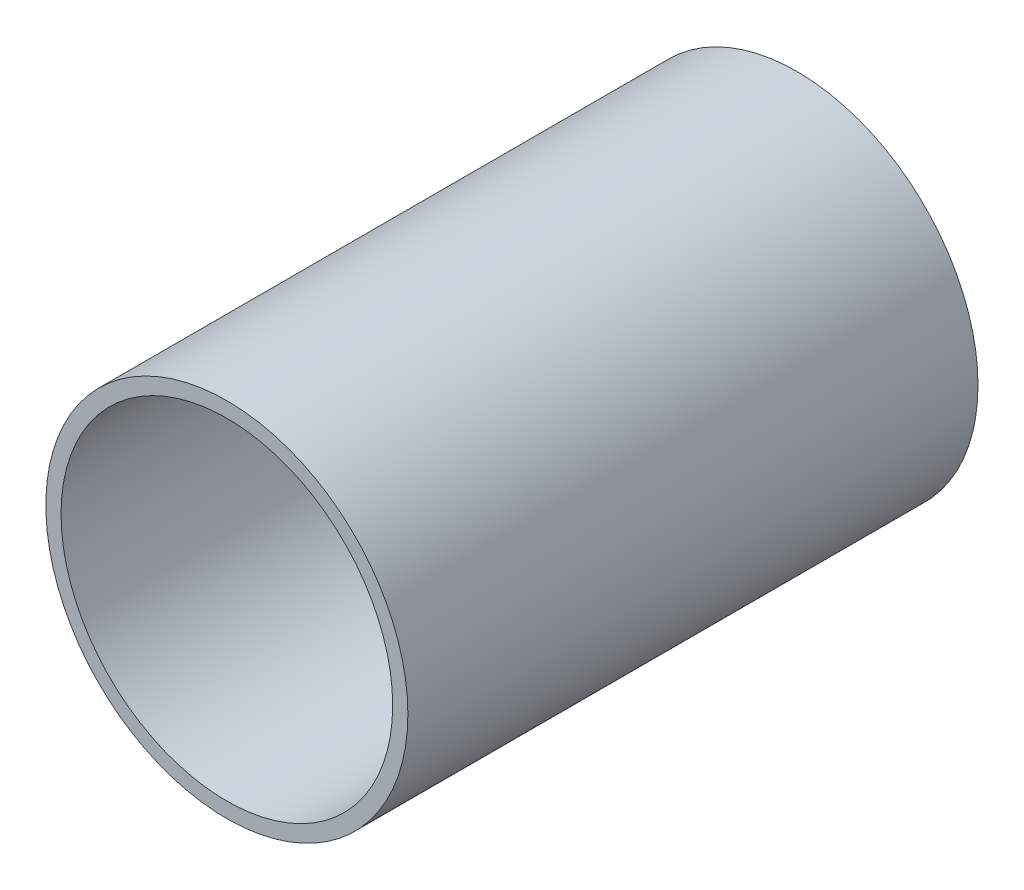
SolidWorks part; units mm, degrees
ref_plane "前基準面" through (0, 0, 0) normal (0, 0, 1) x (1, 0, 0)
ref_plane "上基準面" through (0, 0, 0) normal (0, 1, 0) x (1, 0, 0)
ref_plane "右基準面" through (0, 0, 0) normal (1, 0, 0) x (0, 0, -1)
sketch "草圖1" plane through (0, 0, 0) normal (0, 0, 1) x (1, 0, 0)
  circle A0 centre (0, 0) radius 19.05
  circle A1 centre (0, 0) radius 17.45
  dimension "D1" = 34.9
  dimension "D2" = 38.1
extrude "填料-伸長1" add sketch "草圖1" along normal blind 60
